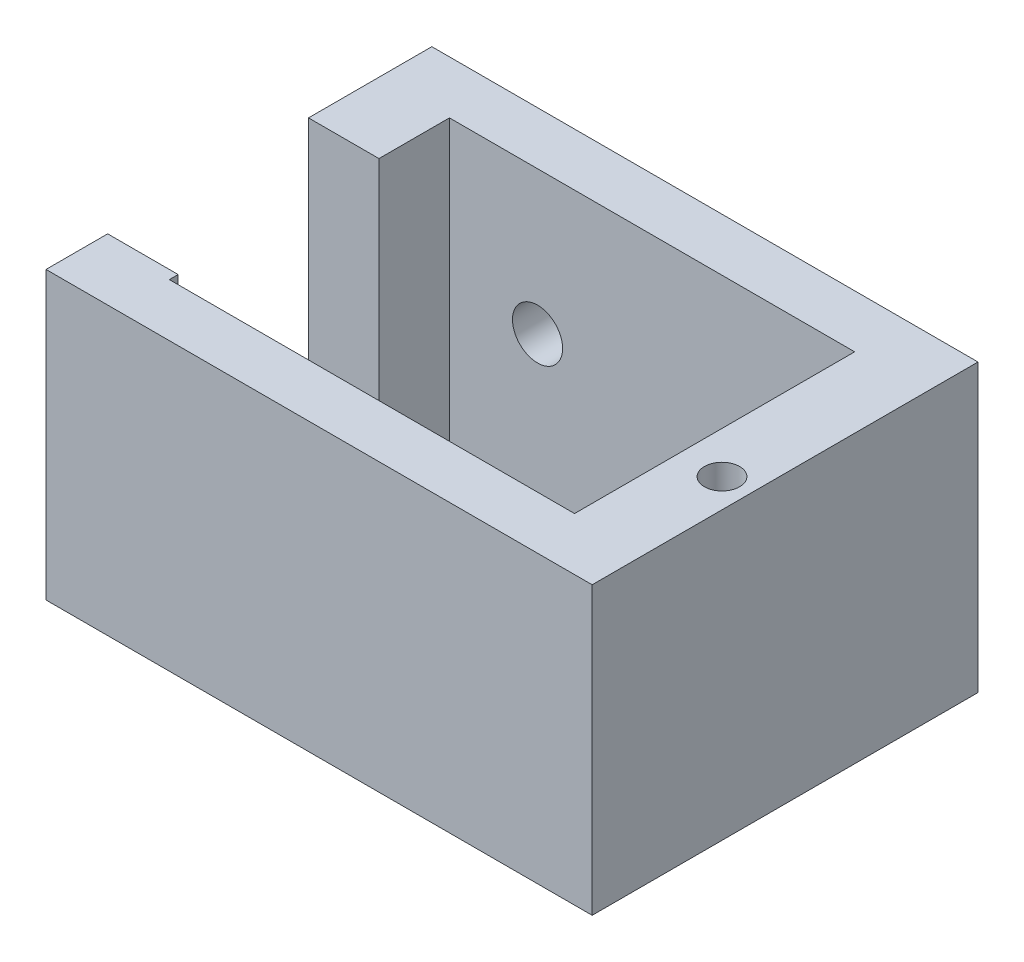
SolidWorks part; units mm, degrees
ref_plane "Front Plane" through (0, 0, 0) normal (0, 0, 1) x (1, 0, 0)
ref_plane "Top Plane" through (0, 0, 0) normal (0, 1, 0) x (1, 0, 0)
ref_plane "Right Plane" through (0, 0, 0) normal (1, 0, 0) x (0, 0, -1)
sketch "Sketch2" plane through (0, 0, 0) normal (0, 1, 0) x (1, 0, 0)
  line L1 (-15.5, -10.95) -> (15.5, -10.95)
  line L2 (-15.5, -10.95) -> (-15.5, 10.95)
  line L3 (-15.5, 10.95) -> (15.5, 10.95)
  line L4 (15.5, -10.95) -> (15.5, 10.95)
  line L5 (-15.5, -10.95) -> (15.5, 10.95) construction
  line L6 (-15.5, 10.95) -> (15.5, -10.95) construction
  point P0 (0, 0)
  dimension "D1" = 31
  dimension "D2" = 21.9
extrude "Boss-Extrude1" add sketch "Sketch2" along normal blind 16.25
sketch "Sketch3" plane through (0, 16.25, 0) normal (0, 1, 0) x (1, 0, 0)
  line L0 (15.5, -10.95) -> (15.5, 10.95) construction
  line L1 (-11.5, -7.95) -> (11.5, -7.95)
  line L2 (-11.5, -7.95) -> (-11.5, 7.95)
  line L3 (-11.5, 7.95) -> (11.5, 7.95)
  line L4 (11.5, -7.95) -> (11.5, 7.95)
  line L5 (-11.5, -7.95) -> (11.5, 7.95) construction
  line L6 (-11.5, 7.95) -> (11.5, -7.95) construction
  line L7 (-15.5, -10.95) -> (15.5, -10.95) construction
  point P0 (0, 0)
  dimension "D1" = 4
  dimension "D2" = 3
extrude "Cut-Extrude1" cut sketch "Sketch3" against normal through all
sketch "Sketch6" plane through (0, 0, -10.95) normal (0, 0, -1) x (-1, 0, 0)
  line L0 (-15.5, 16.25) -> (15.5, 16.25) construction
  line L3 (15.5, 16.25) -> (15.5, 0) construction
  circle A0 centre (-6.5, 8.125) radius 1.4224
  circle A1 centre (6.5, 8.125) radius 1.4224
  point P6 (-3.3985, 8.125)
  dimension "D1" = 2.8448
  dimension "D2" = 2.8448
  dimension "D6" = 9
  dimension "D3" = 8.125
  dimension "D4" = 13
  dimension "D5" = 8.125
extrude "Cut-Extrude3" cut sketch "Sketch6" against normal blind 10
sketch "Sketch7" plane through (-15.5, 0, 0) normal (-1, 0, 0) x (0, 0, 1)
  line L1 (-3.95, 12.75) -> (7.45, 12.75)
  line L2 (-3.95, 12.75) -> (-3.95, 3.5)
  line L3 (-3.95, 3.5) -> (7.45, 3.5)
  line L4 (7.45, 12.75) -> (7.45, 3.5)
  line L6 (10.95, 16.25) -> (10.95, 0) construction
  line L7 (-10.95, 16.25) -> (10.95, 16.25) construction
  line L8 (-10.95, 0) -> (10.95, 0) construction
  line L9 (-10.95, 16.25) -> (-10.95, 0) construction
  dimension "D1" = 3.5
  dimension "D2" = 3.5
  dimension "D3" = 3.5
  dimension "D4" = 7
extrude "Cut-Extrude4" cut sketch "Sketch7" against normal blind 10
sketch "Sketch9" plane through (0, 16.25, 0) normal (0, 1, 0) x (1, 0, 0)
  line L0 (-15.5, 10.95) -> (-15.5, -10.95) construction
  line L1 (15.5, -10.95) -> (15.5, 10.95) construction
  line L2 (-15.5, -10.95) -> (15.5, -10.95) construction
  circle A0 centre (-13.37, -1.95) radius 1
  circle A1 centre (13.87, -1.95) radius 1
  dimension "D5" = 2
  dimension "D1" = 2.13
  dimension "D2" = 1.63
  dimension "D3" = 9
  dimension "D4" = 9
extrude "Cut-Extrude5" cut sketch "Sketch9" against normal blind 10
sketch "Sketch12" plane through (-15.5, 0, 0) normal (-1, 0, 0) x (0, 0, 1)
  line L5 (-10.95, 16.25) -> (10.95, 16.25) construction
  line L10 (-3.95, 12.75) -> (7.45, 12.75)
  line L11 (-3.95, 12.75) -> (-3.95, 16.25)
  line L12 (-3.95, 16.25) -> (7.45, 16.25)
  line L13 (7.45, 12.75) -> (7.45, 16.25)
extrude "Cut-Extrude8" cut sketch "Sketch12" against normal blind 4
